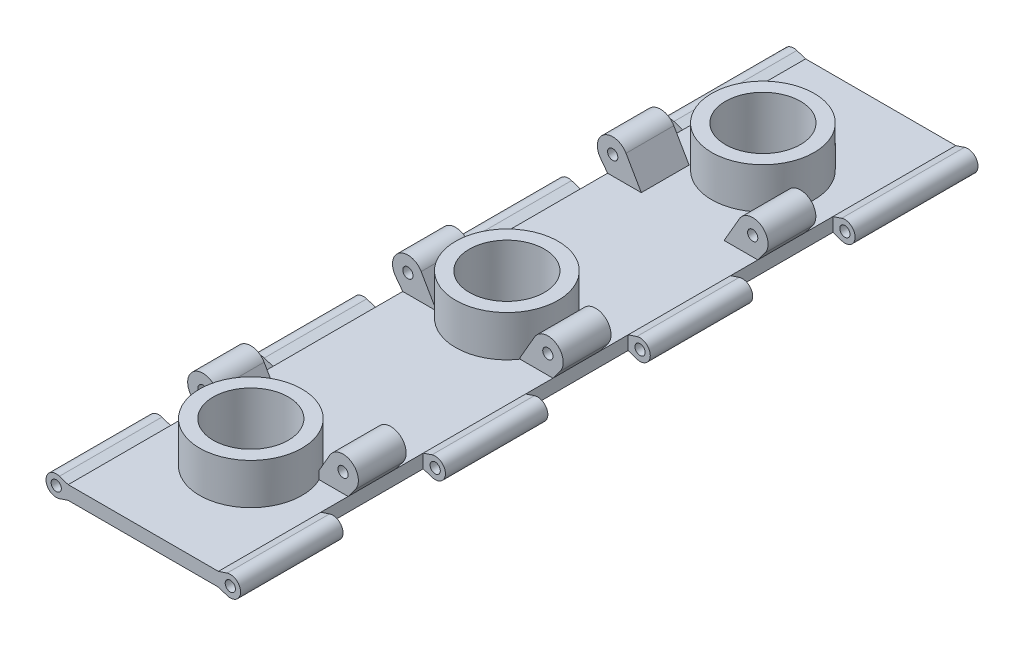
SolidWorks part; units mm, degrees
ref_plane "Płaszczyzna przednia" through (0, 0, 0) normal (0, 0, 1) x (1, 0, 0)
ref_plane "Płaszczyzna górna" through (0, 0, 0) normal (0, 1, 0) x (1, 0, 0)
ref_plane "Płaszczyzna prawa" through (0, 0, 0) normal (1, 0, 0) x (0, 0, -1)
sketch "Sketch1" plane through (0, 0, 0) normal (0, 0, 1) x (1, 0, 0)
  line L0 (0, -9.4894) -> (22, -9.4894)
  line L1 (0, -13.4894) -> (22, -13.4894)
  line L2 (22, -13.4894) -> (22, -14.4894)
  line L3 (16.5, -23.4894) -> (0, -23.4894)
  line L4 (22, -14.4894) -> (16.5, -23.4894)
  line L5 (0, -13.4894) -> (0, -23.4894)
  line L16 (22, -13.4894) -> (22, -9.4894)
  line L17 (16.5, -23.4894) -> (22, -14.4894)
  line L21 (22, -9.4894) -> (24.5557, -8.6418)
  line L22 (0, 7.9714) -> (0, -34.676) construction
  line L23 (22, -13.4894) -> (24.5557, -14.3369)
  circle A1 centre (25.5, -11.4894) radius 3
  circle A2 centre (25.5, -11.4894) radius 1.5
  point P4 (22, -23.4894)
  point P9 (-0.2, -13.2894)
  point P10 (22.2, -13.2894)
  point P13 (-0.2, -23.6894)
  point P14 (18.8555, -27.6894)
  point P15 (-4.2, -27.6894)
  point P16 (-4.2, -9.2894)
  point P17 (26.2, -9.2894)
  point P28 (0, 0)
  dimension "D7" = 6
  dimension "D9" = 2
  dimension "D10" = 3
  dimension "D1" = 9
  dimension "D2" = 5.5
  dimension "D3" = 10
  dimension "D4" = 3.5
  dimension "D6" = 4
  dimension "D17" = 22
extrude "Boss-Extrude1" add sketch "Sketch1" against normal blind 210 contours L0 L22 L1 L16 | A1 L21 L16 L23 | A1 A2
ref_plane "Plane1" through (0, 0, -30) normal (0, 0, 1) x (1, 0, 0)
sketch "Sketch2" plane through (0, 0, -30) normal (0, 0, 1) x (1, 0, 0)
  line L0 (22, -9.4894) -> (22, -13.4894)
  line L2 (22, -6.1485) -> (29.3481, -6.1485)
  line L3 (22, -6.1485) -> (22, -16.1984)
  line L4 (22, -16.1984) -> (29.3481, -16.1984)
  line L5 (29.3481, -6.1485) -> (29.3481, -16.1984)
  circle A2 centre (25.5, -11.4894) radius 1.5
  circle A3 centre (25.5, -11.4894) radius 1.5 construction
extrude "Cut-Extrude2" cut sketch "Sketch2" against normal blind 30 contours L5 L2 L3 L0 L4 A2
pattern_linear "LPattern1" count 3 spacing 60 along (0, 0, -1) of "Cut-Extrude2"
ref_plane "Plane2" through (0, 0, -38) normal (0, 0, 1) x (1, 0, 0)
sketch "Sketch5" plane through (0, 0, -38) normal (0, 0, 1) x (1, 0, 0)
  line L0 (16.6029, -1.7394) -> (12.1284, -9.4894)
  line L1 (0, -9.4894) -> (22, -9.4894) construction
  line L2 (24.1, -6.6894) -> (22, -9.4894)
  line L3 (12.1284, -9.4894) -> (22, -9.4894)
  circle A0 centre (20.5, -3.9894) radius 4.5
  circle A1 centre (20.5, -3.9894) radius 1.5
  circle A3 centre (25.5, -11.4894) radius 1.5 construction
  circle A4 centre (25.5, -11.4894) radius 1.5 construction
  point P13 (8.3004, -9.4894)
  dimension "D1" = 9
  dimension "D5" = 3
  dimension "D2" = 5
  dimension "D3" = 5.5
  dimension "D4" = 60
extrude "Boss-Extrude2" add sketch "Sketch5" against normal blind 14 contours A0 L0 L3 L2 | A0 A1
pattern_linear "LPattern2" count 3 spacing 60 along (0, 0, -1) of "Boss-Extrude2"
mirror "Mirror3" about plane through (0, 0, -210) normal (-1, 0, 0) of "LPattern2", "Boss-Extrude2", "LPattern1", "Cut-Extrude2", "Boss-Extrude1"
sketch "Sketch6" plane through (0, -9.4894, 0) normal (0, 1, 0) x (1, 0, 0)
  line L0 (0, 210) -> (0, 0) construction
  line L1 (-22, 210) -> (22, 210) construction
  circle A0 centre (0, 181.5) radius 11
  circle A1 centre (0, 181.5) radius 15
  point P4 (0, 210)
  point P8 (0, 0)
  point P9 (0, 0)
  point P10 (0, 0)
  point P13 (0, 0)
  dimension "D1" = 22
  dimension "D2" = 28.5
  dimension "D3" = 4
extrude "Boss-Extrude3" add sketch "Sketch6" along normal blind 12
sketch "Sketch9" plane through (0, -9.4894, 0) normal (0, 1, 0) x (1, 0, 0)
  circle A0 centre (0, 181.5) radius 11
  circle A1 centre (0, 181.5) radius 11 construction
  dimension "D1" = 22
extrude "Cut-Extrude4" cut sketch "Sketch9" against normal mid plane 81
pattern_linear "LPattern4" count 3 spacing 75 along (0, 0, 1) of "Boss-Extrude3"
pattern_linear "LPattern5" count 3 spacing 75 along (0, 0, 1) of "Cut-Extrude4"
sketch "Sketch15" plane through (0, 0, 0) normal (0, 0, 1) x (1, 0, 0)
  line L0 (-22, -9.4894) -> (22, -9.4894)
  line L1 (-22, -13.4894) -> (22, -13.4894)
  line L2 (-24.5557, -14.3369) -> (-22, -13.4894)
  line L3 (-24.5557, -8.6418) -> (-22, -9.4894)
  line L4 (0, -1.8725) -> (0, -28.0894) construction
  line L5 (-22, -13.4894) -> (22, -13.4894) construction
  line L6 (-22, -9.4894) -> (22, -9.4894) construction
  line L7 (24.5557, -14.3369) -> (22, -13.4894)
  line L8 (24.5557, -8.6418) -> (22, -9.4894)
  arc A1 (24.5557, -8.6418) -> (24.5557, -14.3369) centre (25.5, -11.4894) cw
  arc A2 (-24.5557, -8.6418) -> (-24.5557, -14.3369) centre (-25.5, -11.4894) ccw
  arc A3 (-24.5557, -8.6418) -> (-24.5557, -14.3369) centre (-25.5, -11.4894) ccw construction
  point P10 (3.4981, -28.0894)
  point P16 (0, -13.4894)
  point P21 (0, -13.4894)
  point P25 (0, -9.4894)
extrude "Boss-Extrude4" add sketch "Sketch15" along normal blind 6
sketch "Sketch16" plane through (0, 0, 6) normal (0, 0, 1) x (1, 0, 0)
  line L0 (-22, -13.4894) -> (-22, -14.4894)
  line L1 (-22, -14.4894) -> (-17, -23.4894)
  line L2 (22, -13.4894) -> (22, -14.4894)
  line L3 (0, -13.4894) -> (0, -33.516) construction
  line L4 (-22, -13.4894) -> (22, -13.4894) construction
  line L5 (-17, -23.4894) -> (17, -23.4894)
  line L6 (-22, -13.4894) -> (22, -13.4894)
  line L7 (22, -14.4894) -> (17, -23.4894)
  point P11 (0, -13.4894)
  point P12 (0, -23.4894)
  dimension "D1" = 1
  dimension "D2" = 9
  dimension "D3" = 5
extrude "Boss-Extrude5" add sketch "Sketch16" against normal blind 3
ref_plane "Plane3" through (0, 0, -105) normal (0, 0, -1) x (-1, 0, 0)
mirror "Mirror6" about plane through (0, 0, -105) normal (0, 0, -1) of "Boss-Extrude5", "Boss-Extrude4"
sketch "Sketch20" plane through (0, 0, 6) normal (0, 0, 1) x (1, 0, 0)
  line L1 (-109.879, 17.5833) -> (61.378, 17.5833)
  line L2 (-109.879, 17.5833) -> (-109.879, -48.9586)
  line L3 (-109.879, -48.9586) -> (61.378, -48.9586)
  line L4 (61.378, 17.5833) -> (61.378, -48.9586)
extrude "Cut-Extrude7" cut sketch "Sketch20" against normal blind 6
